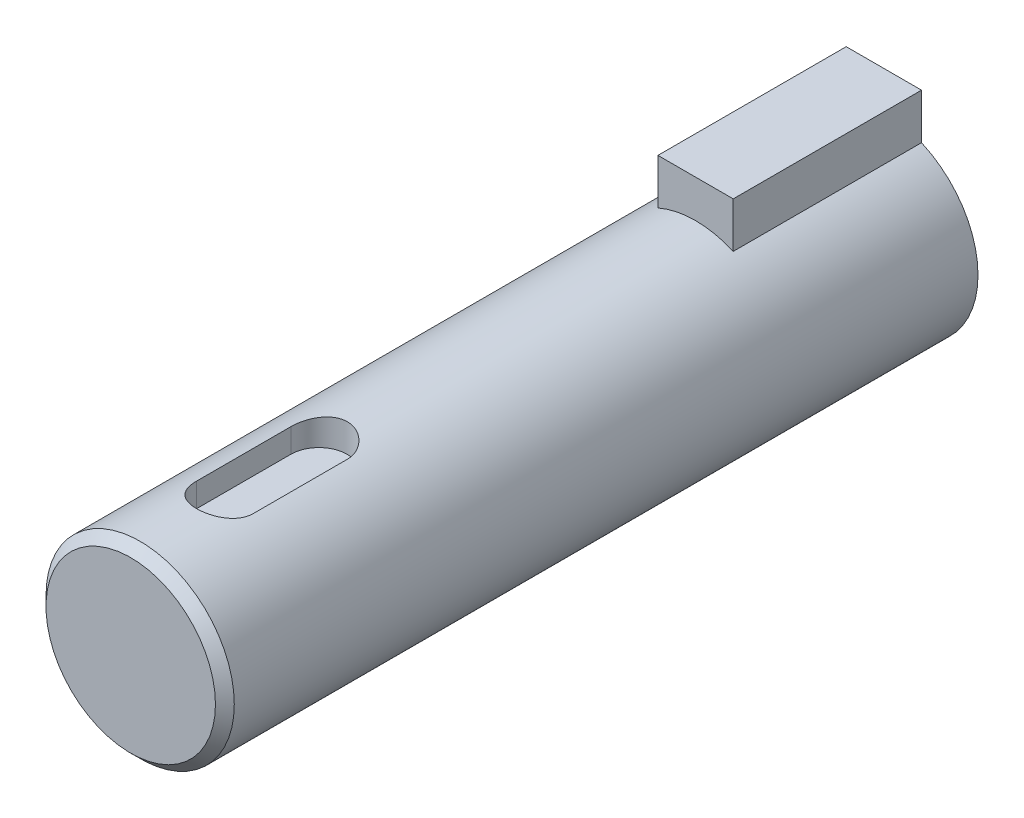
SolidWorks part; units mm, degrees
ref_plane "Front Plane" through (0, 0, 0) normal (0, 0, 1) x (1, 0, 0)
ref_plane "Top Plane" through (0, 0, 0) normal (0, 1, 0) x (1, 0, 0)
ref_plane "Right Plane" through (0, 0, 0) normal (1, 0, 0) x (0, 0, -1)
sketch "Sketch1" plane through (0, 0, 0) normal (0, 0, 1) x (1, 0, 0)
  line L0 (0, 0) -> (0, 7.8765) construction
  line L2 (-2, 7) -> (2, 7)
  line L3 (-2, 7) -> (-2, 4.5826)
  line L5 (2, 7) -> (2, 4.5826)
  arc A0 (-2, 4.5826) -> (2, 4.5826) centre (0, 0) ccw
  dimension "D1" = 10
  dimension "D2" = 4
  dimension "D3" = 7
extrude "Boss-Extrude1" add sketch "Sketch1" along normal blind 10
sketch "Sketch2" plane through (0, 0, 10) normal (0, 0, 1) x (1, 0, 0)
  circle A0 centre (0, 0) radius 5
extrude "Boss-Extrude2" add sketch "Sketch2" along normal blind 30
sketch "Sketch3" plane through (0, 0, 0) normal (0, 1, 0) x (1, 0, 0)
  line L0 (0, -40) -> (0, -17.3088) construction
  line L1 (-5, -40) -> (5, -40) construction
  line L2 (0, -30) -> (0, -35) construction
  line L3 (1.5, -30) -> (1.5, -35)
  line L4 (-1.5, -30) -> (-1.5, -35)
  arc A0 (1.5, -30) -> (-1.5, -30) centre (0, -30) ccw
  arc A1 (-1.5, -35) -> (1.5, -35) centre (0, -35) ccw
  point P7 (0, -32.5)
  dimension "D1" = 3
  dimension "D2" = 5
  dimension "D3" = 5
extrude "Cut-Extrude1" cut sketch "Sketch3" along normal through all from offset 3.5
chamfer "Chamfer1" distance 0.5 angle 45 1 edges at (5, 0, 40)
